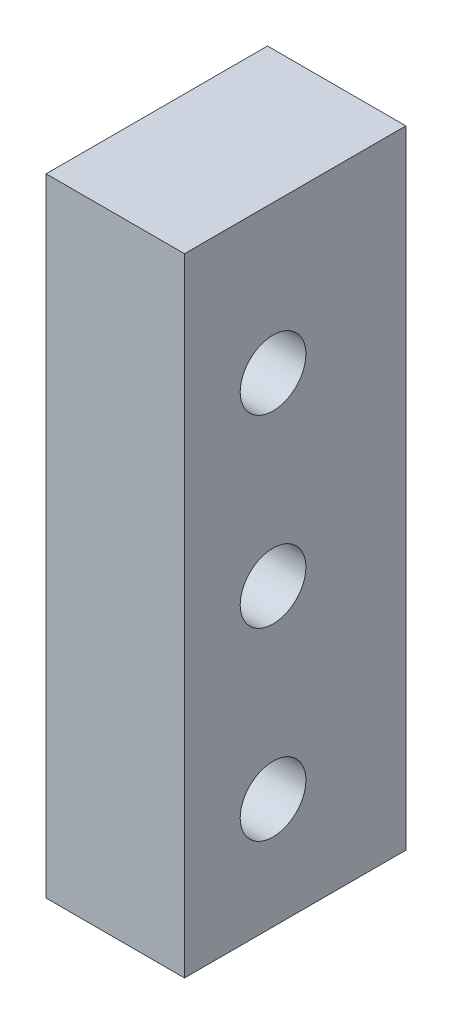
SolidWorks part; units mm, degrees
ref_plane "Front Plane" through (0, 0, 0) normal (0, 0, 1) x (1, 0, 0)
ref_plane "Top Plane" through (0, 0, 0) normal (0, 1, 0) x (1, 0, 0)
ref_plane "Right Plane" through (0, 0, 0) normal (1, 0, 0) x (0, 0, -1)
sketch "Sketch1" plane through (0, 0, 0) normal (1, 0, 0) x (0, 0, -1)
  line L1 (-2.5874, -11.5346) -> (5.0326, -11.5346)
  line L2 (-2.5874, -11.5346) -> (-2.5874, 10.0554)
  line L3 (-2.5874, 10.0554) -> (5.0326, 10.0554)
  line L4 (5.0326, -11.5346) -> (5.0326, 10.0554)
  line L5 (-2.5874, -11.5346) -> (5.0326, 10.0554) construction
  line L6 (-2.5874, 10.0554) -> (5.0326, -11.5346) construction
  circle A0 centre (0.4606, 4.9754) radius 1.1303
  circle A1 centre (0.4606, -1.3746) radius 1.1303
  circle A2 centre (0.4606, -7.7246) radius 1.1303
  dimension "D1" = 5.08
  dimension "D2" = 3.048
  dimension "D3" = 7.62
  dimension "D4" = 21.59
  dimension "D5" = 6.35
  dimension "D6" = 6.35
extrude "Boss-Extrude1" add sketch "Sketch1" along normal blind 4.7625
